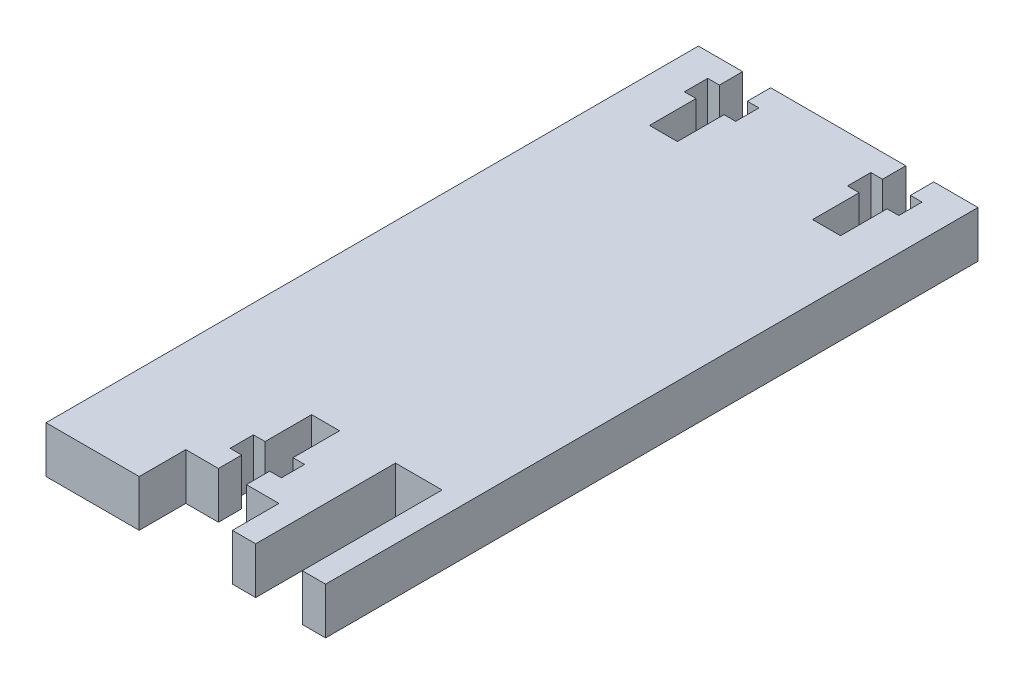
SolidWorks part; units mm, degrees
ref_plane "Front Plane" through (0, 0, 0) normal (0, 0, 1) x (1, 0, 0)
ref_plane "Top Plane" through (0, 0, 0) normal (0, 1, 0) x (1, 0, 0)
ref_plane "Right Plane" through (0, 0, 0) normal (1, 0, 0) x (0, 0, -1)
sketch "Sketch1" plane through (0, 0, 0) normal (0, 0, 1) x (1, 0, 0)
  line L0 (46.394, -153) -> (46.394, -121) construction
  line L1 (46.394, -139.5) -> (16.394, -139.5)
  line L2 (46.394, -139.5) -> (46.394, -134.5)
  line L3 (46.394, -134.5) -> (16.394, -134.5)
  line L4 (16.394, -139.5) -> (16.394, -134.5)
  line L5 (16.394, -153) -> (16.394, -125) construction
  line L6 (22.644, -137) -> (16.394, -137) construction
  dimension "D1" = 5
extrude "Boss-Extrude1" add sketch "Sketch1" along normal blind 65
sketch "Sketch2" plane through (0, -139.5, 0) normal (0, -1, 0) x (1, 0, 0)
  line L0 (21.144, -5) -> (24.144, -5) construction
  line L1 (21.144, -5) -> (24.144, -5) construction
  line L2 (38.644, -5) -> (41.644, -5) construction
  line L3 (38.644, -5) -> (41.644, -5) construction
  line L4 (22.644, -5) -> (22.644, 22.4597) construction
  line L5 (40.144, -5) -> (40.144, 22.4597) construction
  line L6 (16.394, 0) -> (46.394, 0) construction
  line L7 (21.144, 10) -> (24.144, 10)
  line L8 (21.144, 10) -> (21.144, 5)
  line L9 (21.144, 0) -> (24.144, 0)
  line L10 (24.144, 10) -> (24.144, 5)
  line L11 (21.144, 10) -> (24.144, 0) construction
  line L12 (21.144, 0) -> (24.144, 10) construction
  line L13 (31.394, 65) -> (31.394, 0) construction
  line L14 (19.894, 2.5) -> (21.144, 2.5)
  line L15 (19.894, 2.5) -> (19.894, 5)
  line L16 (19.894, 5) -> (21.144, 5)
  line L17 (25.394, 2.5) -> (25.394, 5)
  line L18 (19.894, 2.5) -> (25.394, 5) construction
  line L19 (19.894, 5) -> (25.394, 2.5) construction
  line L20 (16.394, 65) -> (46.394, 65) construction
  line L21 (24.144, 5) -> (25.394, 5)
  line L22 (24.144, 2.5) -> (24.144, 0)
  line L23 (24.144, 2.5) -> (25.394, 2.5)
  line L24 (21.144, 2.5) -> (21.144, 0)
  line L25 (41.644, 10) -> (38.644, 10)
  line L26 (41.644, 10) -> (41.644, 5)
  line L27 (42.894, 5) -> (41.644, 5)
  line L28 (42.894, 2.5) -> (42.894, 5)
  line L29 (42.894, 2.5) -> (41.644, 2.5)
  line L30 (41.644, 2.5) -> (41.644, 0)
  line L31 (41.644, 0) -> (38.644, 0)
  line L32 (38.644, 2.5) -> (38.644, 0)
  line L33 (38.644, 2.5) -> (37.394, 2.5)
  line L34 (37.394, 2.5) -> (37.394, 5)
  line L35 (38.644, 5) -> (37.394, 5)
  line L36 (38.644, 10) -> (38.644, 5)
  point P8 (22.644, 5)
  point P15 (22.644, 3.75)
  dimension "D1" = 2.5
  dimension "D2" = 2.5
  dimension "D3" = 10
  dimension "D4" = 3
  dimension "D5" = 5.5
extrude "Cut-Extrude1" cut sketch "Sketch2" against normal through all
sketch "Sketch3" plane through (0, -139.5, 0) normal (0, -1, 0) x (1, 0, 0)
  line L0 (31.394, 65) -> (31.394, 42.5957) construction
  line L1 (16.394, 65) -> (26.394, 65)
  line L2 (16.394, 65) -> (16.394, 70)
  line L3 (16.394, 70) -> (26.394, 70)
  line L4 (26.394, 65) -> (26.394, 70)
  line L5 (16.394, 65) -> (46.394, 65) construction
  line L6 (36.394, 65) -> (36.394, 70)
  line L7 (46.394, 70) -> (36.394, 70)
  line L8 (46.394, 65) -> (46.394, 70)
  line L9 (46.394, 65) -> (36.394, 65)
  dimension "D1" = 5
  dimension "D2" = 10
extrude "Boss-Extrude2" add sketch "Sketch3" against normal blind 5
sketch "Sketch4" plane through (0, -139.5, 0) normal (0, -1, 0) x (1, 0, 0)
  line L0 (31.394, 65) -> (31.394, 39.4939) construction
  line L1 (26.394, 65) -> (36.394, 65) construction
  line L2 (24.144, 10) -> (21.144, 10) construction
  line L3 (29.894, 55) -> (32.894, 55)
  line L4 (29.894, 55) -> (29.894, 65)
  line L5 (29.894, 65) -> (32.894, 65)
  line L6 (32.894, 55) -> (32.894, 65)
  line L7 (29.894, 55) -> (32.894, 65) construction
  line L8 (29.894, 65) -> (32.894, 55) construction
  line L9 (28.644, 60) -> (34.144, 60)
  line L10 (28.644, 60) -> (28.644, 62.5)
  line L11 (28.644, 62.5) -> (34.144, 62.5)
  line L12 (34.144, 60) -> (34.144, 62.5)
  line L13 (28.644, 60) -> (34.144, 62.5) construction
  line L14 (28.644, 62.5) -> (34.144, 60) construction
  line L15 (25.394, 2.5) -> (25.394, 5) construction
  line L16 (19.894, 5) -> (25.394, 5) construction
  line L17 (38.644, 10) -> (38.644, 0) construction
  point P4 (31.394, 60)
  point P9 (31.394, 61.25)
  line M29 (36.394, 65) -> (26.394, 65)
  dimension "D1" = 2.5
extrude "Cut-Extrude2" cut sketch "Sketch4" against normal through all contours L11 L10 L9 L4 | L4 L11 L6 M29 | L11 L4 L9 L6 | L9 L4 L3 L6 | L9 L12 L11 L6
sketch "Sketch5" plane through (0, -134.5, 0) normal (0, 1, 0) x (1, 0, 0)
  line L0 (46.394, -70) -> (36.394, -70) construction
  line L1 (43.894, -70) -> (38.894, -70)
  line L2 (43.894, -70) -> (43.894, -55)
  line L3 (43.894, -55) -> (38.894, -55)
  line L4 (38.894, -70) -> (38.894, -55)
  dimension "D1" = 5
extrude "Cut-Extrude3" cut sketch "Sketch5" against normal through all
